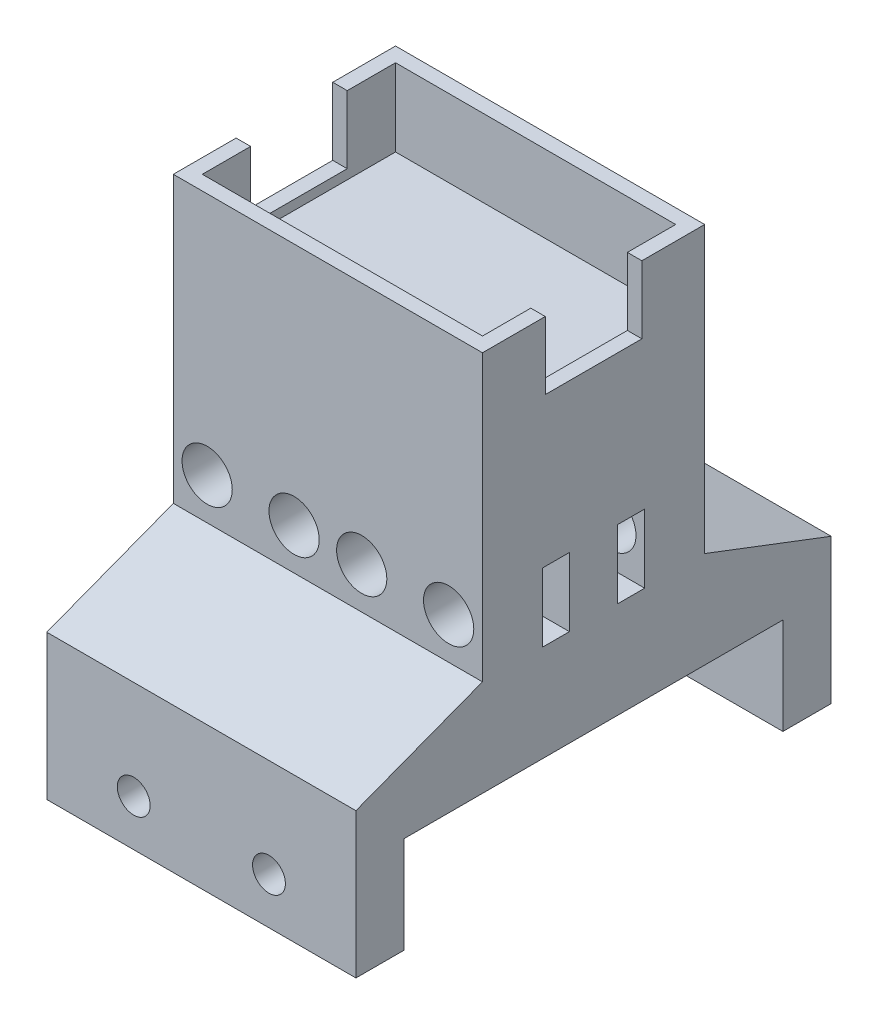
SolidWorks part; units mm, degrees
material "PLA"
ref_plane "Front Plane" through (0, 0, 0) normal (0, 0, 1) x (1, 0, 0)
ref_plane "Top Plane" through (0, 0, 0) normal (0, 1, 0) x (1, 0, 0)
ref_plane "Right Plane" through (0, 0, 0) normal (1, 0, 0) x (0, 0, -1)
sketch "Sketch4" plane through (0, 0, 0) normal (0, 1, 0) x (1, 0, 0)
  line L1 (-16, -11.5) -> (16, -11.5)
  line L2 (-16, -11.5) -> (-16, 11.5)
  line L3 (-16, 11.5) -> (16, 11.5)
  line L4 (16, -11.5) -> (16, 11.5)
  line L5 (-16, -11.5) -> (16, 11.5) construction
  line L6 (-16, 11.5) -> (16, -11.5) construction
  point P0 (0, 0)
  dimension "D1" = 32
  dimension "D2" = 23
extrude "Boss-Extrude3" add sketch "Sketch4" along normal blind 19.5
sketch "Sketch5" plane through (0, 19.5, 0) normal (0, 1, 0) x (1, 0, 0)
  line L1 (-14.5, -10) -> (14.5, -10)
  line L2 (-14.5, -10) -> (-14.5, 10)
  line L3 (-14.5, 10) -> (14.5, 10)
  line L4 (14.5, -10) -> (14.5, 10)
  line L5 (-14.5, -10) -> (14.5, 10) construction
  line L6 (-14.5, 10) -> (14.5, -10) construction
  point P0 (0, 0)
  dimension "D1" = 29
  dimension "D2" = 20
extrude "Cut-Extrude2" cut sketch "Sketch5" against normal blind 8
sketch "Sketch7" plane through (16, 0, 0) normal (1, 0, 0) x (0, 0, -1)
  line L1 (-5, 12.5) -> (5, 12.5)
  line L2 (-5, 12.5) -> (-5, 19.5)
  line L3 (-5, 19.5) -> (5, 19.5)
  line L4 (5, 12.5) -> (5, 19.5)
  line L5 (-11.5, 19.5) -> (11.5, 19.5) construction
  point P6 (0, 19.5)
  point P8 (0, 19.5)
  dimension "D1" = 10
  dimension "D2" = 7
extrude "Cut-Extrude4" cut sketch "Sketch7" against normal through all
sketch "Sketch8" plane through (0, 0, 0) normal (0, -1, 0) x (-1, 0, 0)
  line L17 (-16, -11.5) -> (16, -11.5)
  line L18 (-16, -11.5) -> (-16, 11.5)
  line L19 (-16, 11.5) -> (16, 11.5)
  line L20 (16, -11.5) -> (16, 11.5)
  line L21 (-16, -11.5) -> (16, 11.5) construction
  line L22 (-16, 11.5) -> (16, -11.5) construction
  point P4 (0, 0)
extrude "Boss-Extrude4" add sketch "Sketch8" along normal blind 10
ref_plane "Plane1" through (0, 0, 0) normal (0, 0, -1) x (-1, 0, 0)
sketch "Sketch12" plane through (0, 0, -11.5) normal (0, 0, -1) x (-1, 0, 0)
  line L0 (0, 19.5) -> (0, -10) construction
  line L1 (-16, 19.5) -> (16, 19.5) construction
  line L2 (16, -10) -> (-16, -10) construction
  line L3 (-16, 19.5) -> (0, -10) construction
  line L4 (0, 19.5) -> (-16, -10) construction
  line L5 (-8, 4.75) -> (-8, -10) construction
  line L6 (-16, 19.5) -> (-16, -10) construction
  circle A0 centre (-12.5, -5.7269) radius 2.6
  circle A1 centre (-3.5, -5.7269) radius 2.6
  circle A2 centre (3.5, -5.7269) radius 2.6
  circle A3 centre (12.5, -5.7269) radius 2.6
  dimension "D1" = 5.2
  dimension "D3" = 3.5
  dimension "D2" = 4.2731
extrude "Cut-Extrude5" cut sketch "Sketch12" against normal blind 7
pattern_circular "CirPattern1" count 2 over 180 about axis through (0, 11.5, 0) along (0, -1, 0) of "Cut-Extrude5"
sketch "Sketch13" plane through (0, -10, 0) normal (0, -1, 0) x (-1, 0, 0)
  line L0 (16, -11.5) -> (16, 11.5) construction
  line L1 (16, 2.5) -> (1, 2.5)
  line L2 (16, 2.5) -> (16, 5.2916)
  line L3 (16, 5.2916) -> (1, 5.2916)
  line L4 (1, 2.5) -> (1, 5.2916)
  line L5 (16, 2.5) -> (1, 5.2916) construction
  line L6 (16, 5.2916) -> (1, 2.5) construction
  line L7 (13.475, 0) -> (-13.475, 0) construction
  line L8 (0, -11.5) -> (0, 11.5) construction
  line L9 (-16, -11.5) -> (16, -11.5) construction
  line L10 (16, 11.5) -> (-16, 11.5) construction
  line L11 (-16, 5.2916) -> (-1, 5.2916)
  line L12 (-1, 2.5) -> (-1, 5.2916)
  line L13 (-16, 2.5) -> (-1, 2.5)
  line L14 (-16, 2.5) -> (-16, 5.2916)
  line L15 (-16, -2.5) -> (-16, -5.2916)
  line L16 (-16, -2.5) -> (-1, -2.5)
  line L17 (-1, -2.5) -> (-1, -5.2916)
  line L18 (-16, -5.2916) -> (-1, -5.2916)
  line L19 (16, -5.2916) -> (1, -5.2916)
  line L20 (1, -2.5) -> (1, -5.2916)
  line L21 (16, -2.5) -> (1, -2.5)
  line L22 (16, -2.5) -> (16, -5.2916)
  point P4 (8.5, 3.8958)
  dimension "D1" = 15
  dimension "D2" = 2.7916
  dimension "D3" = 2.5
extrude "Cut-Extrude6" cut sketch "Sketch13" against normal blind 7.1
sketch "Sketch14" plane through (0, -10, 0) normal (0, -1, 0) x (-1, 0, 0)
  line L1 (16, 11.5) -> (-16, 11.5)
  line L2 (16, 11.5) -> (16, -11.5)
  line L3 (16, -11.5) -> (-16, -11.5)
  line L4 (-16, 11.5) -> (-16, -11.5)
  line L5 (16, 11.5) -> (-16, -11.5) construction
  line L6 (16, -11.5) -> (-16, 11.5) construction
  point P4 (0, 0)
extrude "Boss-Extrude5" add sketch "Sketch14" along normal blind 5
sketch "Sketch15" plane through (-16, 0, 0) normal (-1, 0, 0) x (0, 0, 1)
  line L1 (-24.6, -15) -> (-24.6, -30)
  line L2 (-24.6, -30) -> (-19.6, -30)
  line L3 (-19.6, -30) -> (-19.6, -20)
  line L4 (-19.6, -20) -> (19.6, -20)
  line L5 (0, -20) -> (0, -15) construction
  line L6 (11.5, -15) -> (-11.5, -15) construction
  line L8 (19.6, -30) -> (19.6, -20)
  line L9 (24.6, -30) -> (19.6, -30)
  line L10 (24.6, -15) -> (24.6, -30)
  line L12 (-24.6, -15) -> (-11.5, -10)
  line L13 (-11.5, 19.5) -> (-11.5, -15) construction
  line L14 (-11.5, -10) -> (-11.5, -15)
  line L15 (-11.5, -15) -> (11.5, -15)
  line L16 (11.5, -10) -> (11.5, -15)
  line L17 (24.6, -15) -> (11.5, -10)
  dimension "D1" = 39.2
  dimension "D2" = 10
  dimension "D3" = 5
  dimension "D4" = 5
extrude "Boss-Extrude6" add sketch "Sketch15" against normal up to surface (32 mm away) up to face at (16, -6.45, -3.8958)
sketch "Sketch16" plane through (0, 0, -24.6) normal (0, 0, -1) x (-1, 0, 0)
  line L0 (0, 0) -> (0, 50000) construction
  line L1 (-16, -20) -> (16, -20) construction
  circle A0 centre (7, -25.2) radius 1.7
  circle A1 centre (-7, -25.2) radius 1.7
  dimension "D1" = 3.4
  dimension "D2" = 7
  dimension "D3" = 5.2
extrude "Cut-Extrude7" cut sketch "Sketch16" against normal through all
